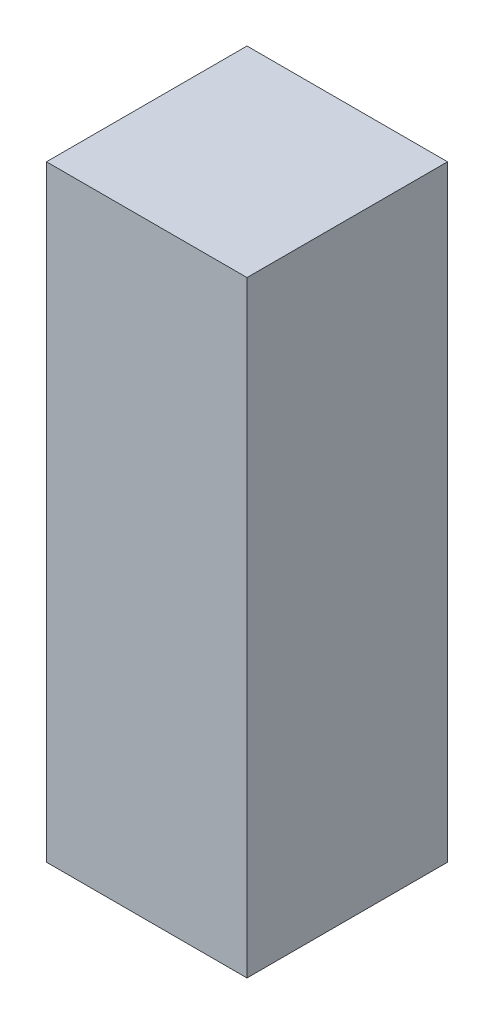
SolidWorks part; units mm, degrees
ref_plane "Front Plane" through (0, 0, 0) normal (0, 0, 1) x (1, 0, 0)
ref_plane "Top Plane" through (0, 0, 0) normal (0, 1, 0) x (1, 0, 0)
ref_plane "Right Plane" through (0, 0, 0) normal (1, 0, 0) x (0, 0, -1)
sketch "Sketch1" plane through (0, 0, 0) normal (0, 1, 0) x (1, 0, 0)
  line L1 (0, 0) -> (20, 0)
  line L2 (0, 0) -> (0, -20)
  line L3 (0, -20) -> (20, -20)
  line L4 (20, 0) -> (20, -20)
extrude "Boss-Extrude1" add sketch "Sketch1" along normal up to surface (60.5013 mm away)
